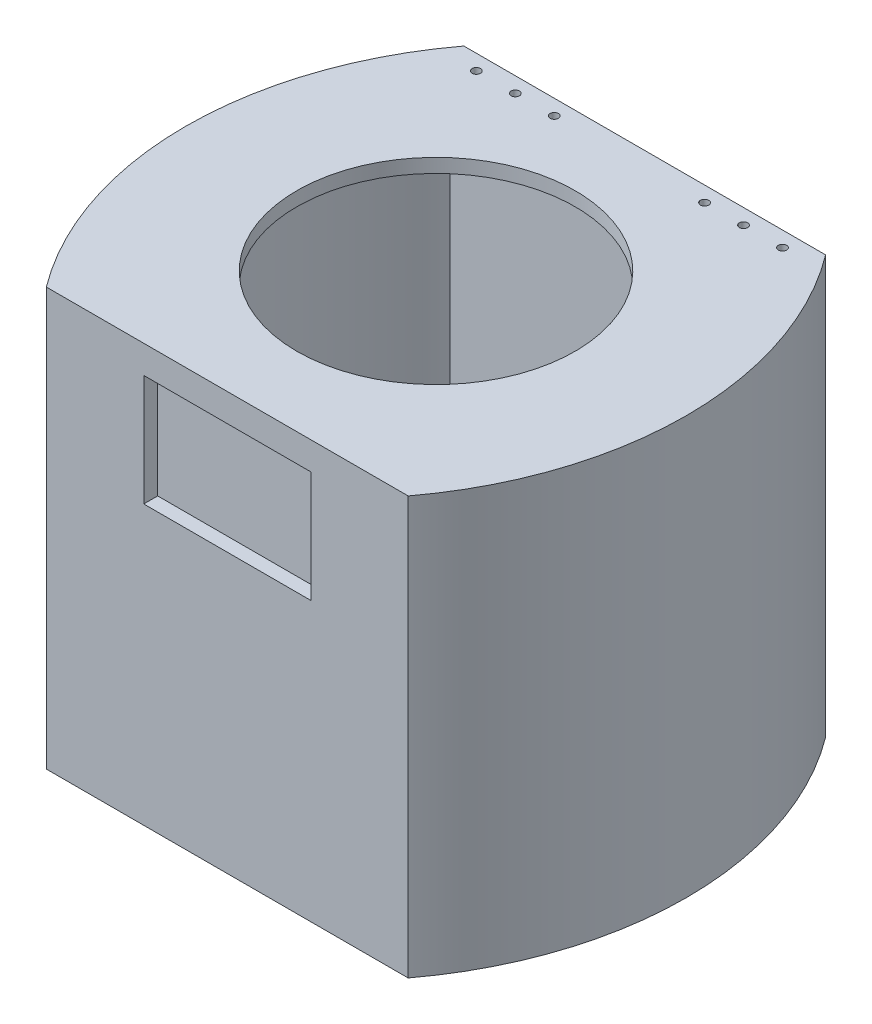
SolidWorks part; units mm, degrees
ref_plane "Front Plane" through (0, 0, 0) normal (0, 0, 1) x (1, 0, 0)
ref_plane "Top Plane" through (0, 0, 0) normal (0, 1, 0) x (1, 0, 0)
ref_plane "Right Plane" through (0, 0, 0) normal (1, 0, 0) x (0, 0, -1)
sketch "Case" plane through (0, 0, 0) normal (0, 1, 0) x (1, 0, 0)
  line L0 (-130, 150) -> (130, 150)
  line L1 (-130, -150) -> (130, -150)
  arc A4 (-130, 150) -> (-130, -150) centre (70, 0) ccw
  arc A5 (130, 150) -> (130, -150) centre (-70, 0) cw
  dimension "D1" = 130
  dimension "D6" = 250
  dimension "D7" = 250
  dimension "D2" = 260
  dimension "D3" = 130
  dimension "D4" = 150
  dimension "D5" = 150
extrude "Boss-Extrude1" add sketch "Case" along normal blind 300
ref_plane "Plane1" through (0, 290, 0) normal (0, 1, 0) x (1, 0, 0)
sketch "Hollow compartment" plane through (0, 290, 0) normal (0, 1, 0) x (1, 0, 0)
  line L0 (-120, 130) -> (120, 130)
  line L1 (-120, -130) -> (120, -130)
  line L2 (-130, -150) -> (130, -150) construction
  line L3 (130, 150) -> (-130, 150) construction
  arc A0 (-120, 130) -> (-120, -130) centre (81.7424, 0) ccw
  arc A1 (120, 130) -> (120, -130) centre (-81.7424, 0) cw
  dimension "D5" = 240
  dimension "D6" = 240
  dimension "D1" = 240
  dimension "D2" = 10
  dimension "D3" = 20
  dimension "D4" = 20
extrude "Cut-Extrude8" cut sketch "Hollow compartment" against normal blind 280
sketch "Compartment Input" plane through (0, 300, 0) normal (0, 1, 0) x (1, 0, 0)
  circle A0 centre (0, 0) radius 100
  dimension "D1" = 200
extrude "Cut-Extrude1" cut sketch "Compartment Input" against normal blind 240
sketch "LCD" plane through (0, 0, 150) normal (0, 0, 1) x (1, 0, 0)
  line L0 (130, 300) -> (130, 0) construction
  line L1 (-60, 280) -> (60, 280)
  line L2 (-60, 280) -> (-60, 200)
  line L3 (-60, 200) -> (60, 200)
  line L4 (60, 280) -> (60, 200)
  line L6 (-130, 0) -> (130, 0) construction
  dimension "D1" = 120
  dimension "D2" = 80
  dimension "D3" = 70
  dimension "D4" = 200
extrude "Cut-Extrude2" cut sketch "LCD" against normal blind 10
sketch "Hinge holes" plane through (0, 300, 0) normal (0, 1, 0) x (1, 0, 0)
  line L0 (130, 150) -> (-130, 150) construction
  circle A0 centre (-110, 139) radius 3
  circle A1 centre (-82, 139) radius 3
  circle A2 centre (-54, 139) radius 3
  circle A3 centre (54, 139) radius 3
  circle A4 centre (82, 139) radius 3
  circle A5 centre (110, 139) radius 3
  dimension "D1" = 6
  dimension "D2" = 28
  dimension "D3" = 28
  dimension "D4" = 28
  dimension "D5" = 28
  dimension "D6" = 11
  dimension "D7" = 20
  dimension "D8" = 20
extrude "Cut-Extrude3" cut sketch "Hinge holes" against normal blind 20
sketch "Power supply holes" plane through (0, 0, 0) normal (0, 1, 0) x (1, 0, 0)
  line L0 (130, 150) -> (-130, 150) construction
  circle A0 centre (-82.5, 40) radius 3.5
  circle A1 centre (37.5, 40) radius 3.5
  circle A2 centre (37.5, -40) radius 3.5
  circle A3 centre (-82.5, -40) radius 3.5
  dimension "D1" = 7
  dimension "D2" = 80
  dimension "D3" = 120
  dimension "D4" = 110
  dimension "D5" = 82.5
sketch "Poles for middle layer" plane through (0, 10, 0) normal (0, 1, 0) x (1, 0, 0)
  circle A0 centre (0, 90) radius 17.5
  circle A1 centre (0, -90) radius 17.5
  dimension "D1" = 35
  dimension "D2" = 90
  dimension "D3" = 90
extrude "Boss-Extrude2" add sketch "Poles for middle layer" along normal blind 110
sketch "Holes for poles" plane through (0, 120, 0) normal (0, 1, 0) x (1, 0, 0)
  circle A0 centre (0, -90) radius 12.5
  circle A1 centre (0, 90) radius 12.5
  dimension "D1" = 25
extrude "Cut-Extrude6" cut sketch "Holes for poles" against normal blind 50
extrude "Cut-Extrude9" cut sketch "Power supply holes" along normal up to next
